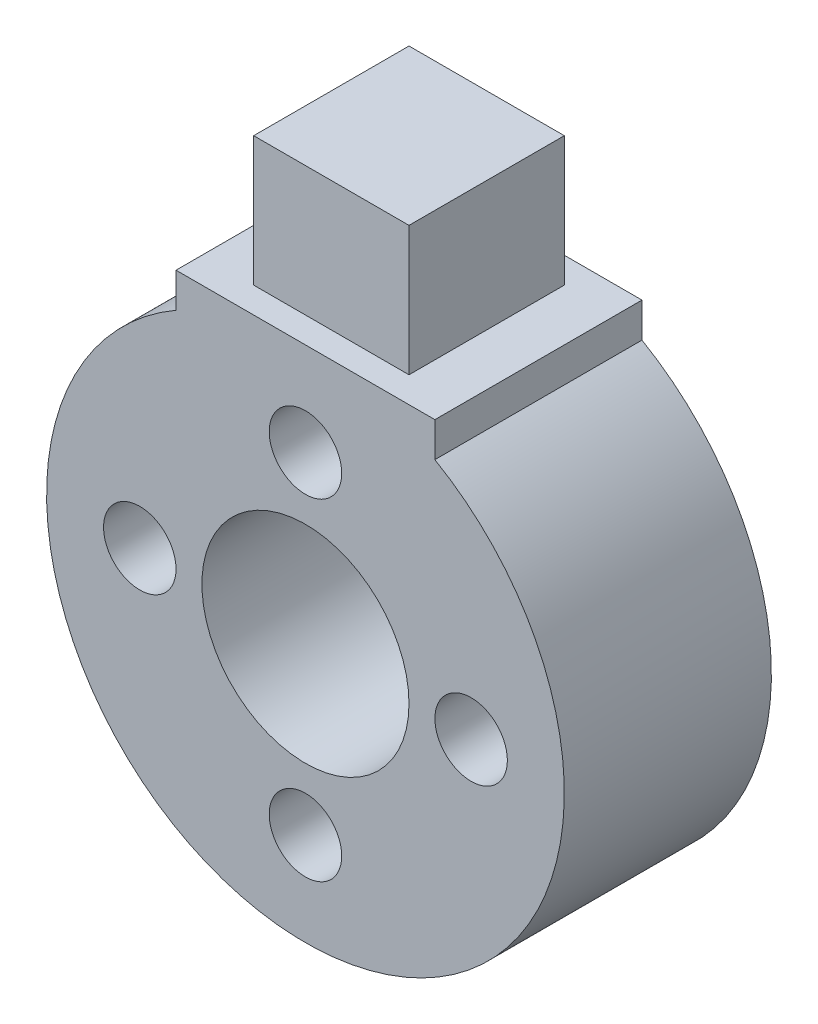
SolidWorks part; units mm, degrees
ref_plane "Front Plane" through (0, 0, 0) normal (0, 0, 1) x (1, 0, 0)
ref_plane "Top Plane" through (0, 0, 0) normal (0, 1, 0) x (1, 0, 0)
ref_plane "Right Plane" through (0, 0, 0) normal (1, 0, 0) x (0, 0, -1)
sketch "Sketch1" plane through (0, 0, 0) normal (0, 0, 1) x (1, 0, 0)
  line L0 (0, 0) -> (0, 12.7) construction
  line L1 (-6.35, 12.7) -> (-6.35, 10.9985)
  line L2 (-6.35, 12.7) -> (6.35, 12.7)
  line L3 (6.35, 12.7) -> (6.35, 10.9985)
  circle A0 centre (0, 0) radius 5.08
  arc A1 (-6.35, 10.9985) -> (6.35, 10.9985) centre (0, 0) ccw
  circle A2 centre (0, 8.128) radius 1.778
  circle A3 centre (8.128, 0) radius 1.778
  circle A4 centre (0, -8.128) radius 1.778
  circle A5 centre (-8.128, 0) radius 1.778
  point P15 (0, 0)
  dimension "D1" = 10.16
  dimension "D2" = 25.4
  dimension "D4" = 3.556
  dimension "D3" = 8.128
  dimension "D6" = 1.7015
  dimension "D8" = 1.7015
  dimension "D5" = 4
extrude "Boss-Extrude1" add sketch "Sketch1" along normal blind 10.16
sketch "Sketch2" plane through (0, 12.7, 0) normal (0, 1, 0) x (1, 0, 0)
  line L0 (6.35, -10.16) -> (6.35, 0) construction
  line L1 (-3.81, -1.27) -> (3.81, -1.27)
  line L2 (-3.81, -1.27) -> (-3.81, -8.89)
  line L3 (-3.81, -8.89) -> (3.81, -8.89)
  line L4 (3.81, -1.27) -> (3.81, -8.89)
  line L5 (-3.81, -1.27) -> (3.81, -8.89) construction
  line L6 (-3.81, -8.89) -> (3.81, -1.27) construction
  line L7 (-6.35, -10.16) -> (6.35, -10.16) construction
  point P0 (0, -5.08)
  dimension "D1" = 7.62
  dimension "D2" = 7.62
  dimension "D3" = 2.54
  dimension "D4" = 1.27
extrude "Boss-Extrude2" add sketch "Sketch2" along normal blind 6.35
